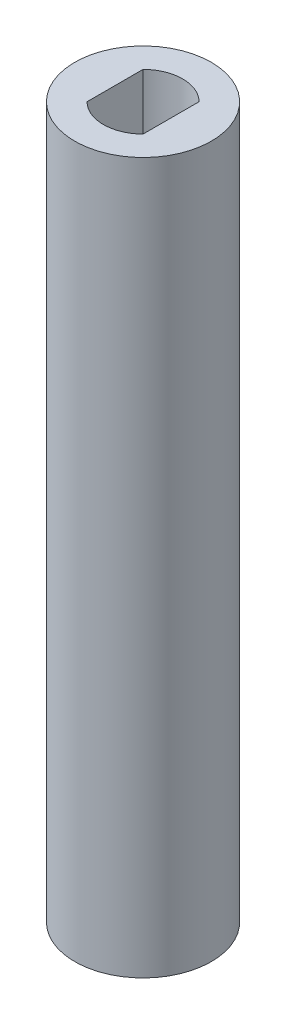
SolidWorks part; units mm, degrees
ref_plane "Front Plane" through (0, 0, 0) normal (0, 0, 1) x (1, 0, 0)
ref_plane "Top Plane" through (0, 0, 0) normal (0, 1, 0) x (1, 0, 0)
ref_plane "Right Plane" through (0, 0, 0) normal (1, 0, 0) x (0, 0, -1)
sketch "Sketch1" plane through (0, 0, 0) normal (0, 1, 0) x (1, 0, 0)
  line L0 (1.85, 1.9666) -> (1.85, -1.9666) construction
  line L1 (-1.85, 1.9666) -> (-1.85, -1.9666) construction
  line L2 (0, 2.7) -> (0, -2.7) construction
  line L3 (-2.05, 2.0512) -> (-2.05, -2.0512)
  line L4 (2.05, 2.0512) -> (2.05, -2.0512)
  arc A1 (1.85, 1.9666) -> (-1.85, 1.9666) centre (0, 0) ccw construction
  circle A2 centre (0, 0) radius 5
  arc A3 (-1.85, -1.9666) -> (1.85, -1.9666) centre (0, 0) ccw construction
  arc A4 (-2.05, -2.0512) -> (2.05, -2.0512) centre (0, 0) ccw
  arc A5 (2.05, 2.0512) -> (-2.05, 2.0512) centre (0, 0) ccw
  dimension "D1" = 5.4
  dimension "D3" = 0.2
  dimension "D4" = 10
  dimension "D2" = 3.7
extrude "Boss-Extrude1" add sketch "Sketch1" along normal blind 52 contours A2 A3 L1 A1 L0
